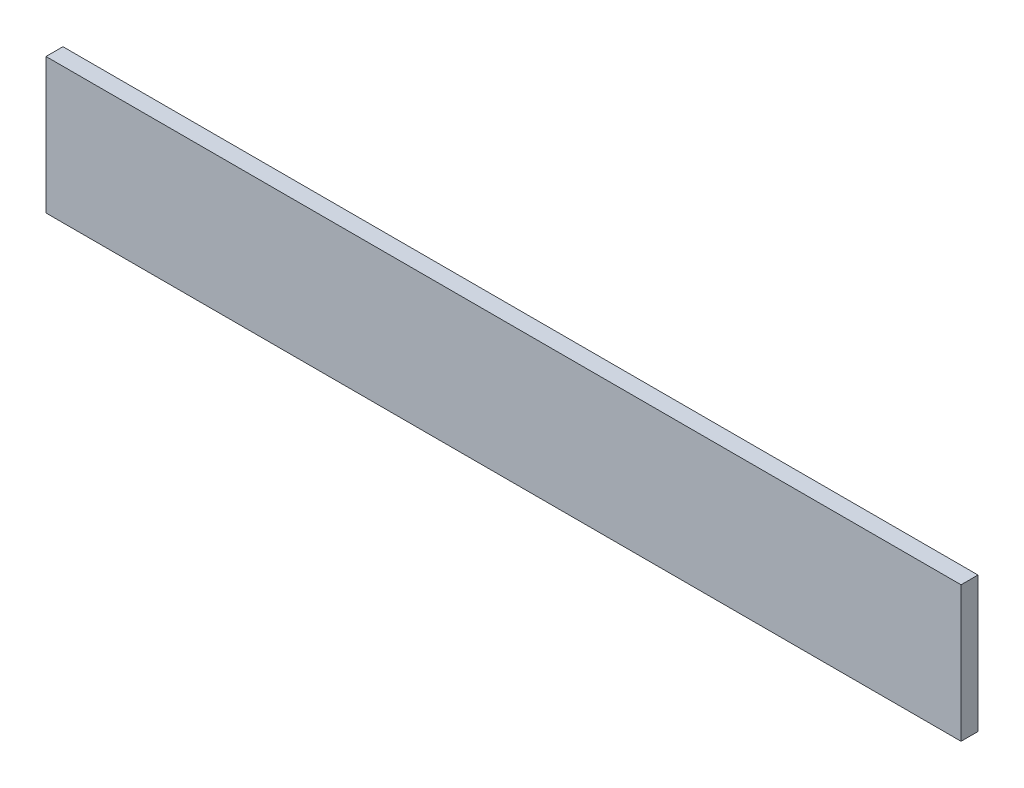
SolidWorks part; units mm, degrees
ref_plane "Plan de face" through (0, 0, 0) normal (0, 0, 1) x (1, 0, 0)
ref_plane "Plan de dessus" through (0, 0, 0) normal (0, 1, 0) x (1, 0, 0)
ref_plane "Plan de droite" through (0, 0, 0) normal (1, 0, 0) x (0, 0, -1)
sketch "Esquisse1" plane through (0, 0, 0) normal (0, 0, 1) x (1, 0, 0)
  line L1 (-135, 90) -> (135, 90)
  line L2 (-135, 90) -> (-135, -90)
  line L3 (-135, -90) -> (135, -90)
  line L4 (135, 90) -> (135, -90)
  line L5 (-135, 90) -> (135, -90) construction
  line L6 (-135, -90) -> (135, 90) construction
  point P0 (0, 0)
  dimension "D1" = 270
  dimension "D2" = 180
extrude "Boss.-Extru.1" add sketch "Esquisse1" along normal blind 5
sketch "Esquisse2" plane through (0, 90, 0) normal (0, 1, 0) x (1, 0, 0)
  line L1 (135, -5) -> (-135, -5)
  line L2 (135, -5) -> (135, 0)
  line L3 (135, 0) -> (-135, 0)
  line L4 (-135, -5) -> (-135, 0)
extrude "Enlèv. mat.-Extru.1" cut sketch "Esquisse2" against normal blind 140
